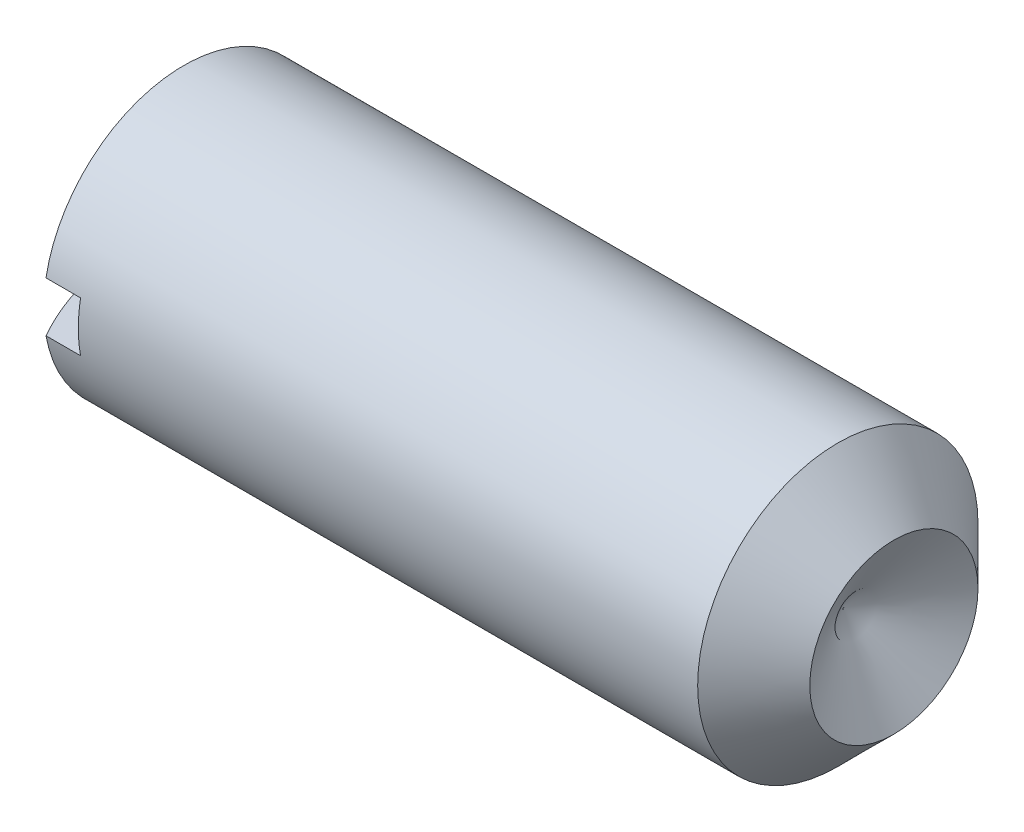
SolidWorks part; units mm, degrees
revolve "BaseBody" add sketch "BodySke" angle 360 about L5
sketch "BodySke" plane through (0, 0, 0) normal (0, 0, 1) x (1, 0, 0)
  line L0 (2.5522, -9.525) -> (47.1574, -9.525) construction
  line L1 (50.8, -5.715) -> (47.3661, 0) construction
  line L2 (2.5522, 9.525) -> (46.99, 9.525)
  line L3 (50.8, 5.715) -> (46.99, 9.525)
  line L4 (47.3661, 0) -> (0, 0)
  line L5 (-12.7, 0) -> (88.9, 0) construction
  line L6 (50.8, 5.715) -> (50.8, 19.05) construction
  line L7 (50.8, -5.715) -> (46.99, -9.525) construction
  line L8 (50.8, 5.715) -> (47.3661, 0)
  line L9 (2.0066, 12.7) -> (2.0066, -3.175) construction
  arc A1 (2.5522, 9.525) -> (0, 0) centre (19.05, 0) ccw
  dimension "Crown_radius" = 19.05
  dimension "Diameter" = 19.05
  dimension "Nose_ch_ang" = 45
  dimension "Length" = 50.8
  dimension "Cup_dia" = 11.43
  dimension "Cup_ang" = 118
  dimension "Advance" = 2.0066
cosmetic thread "ThreadCosmetic" [suppressed] parameters "Thread_minor"=16.0249
extrude "Slot" cut sketch "Sketch2" along normal blind 4.9022
sketch "Sketch2" plane through (0, 0, 0) normal (1, 0, 0) x (0, 0, -1)
  line L1 (9.525, -1.7018) -> (-9.525, -1.7018)
  line L2 (9.525, -1.7018) -> (9.525, 1.7018)
  line L3 (9.525, 1.7018) -> (-9.525, 1.7018)
  line L4 (-9.525, -1.7018) -> (-9.525, 1.7018)
  dimension "D1" = 19.05
  dimension "Slot_width" = 3.4036
  dimension "D3" = 9.525
  dimension "D2" = 1.7018
ref_plane "Plane1" through (0, 0, 0) normal (0, 0, 1) x (1, 0, 0)
ref_plane "Plane2" through (0, 0, 0) normal (0, 1, 0) x (1, 0, 0)
ref_plane "Plane3" through (0, 0, 0) normal (1, 0, 0) x (0, 0, -1)
sketch "ThdSchSke" plane through (0, 0, 0) normal (0, 0, 1) x (1, 0, 0)
  line L0 (2.5522, -8.0124) -> (1.4931, -9.525)
  line L1 (2.5522, -8.0124) -> (3.6113, -9.525)
  line L2 (3.6113, -9.525) -> (3.6113, -11.9063)
  line L3 (-3.175, 0) -> (5.1513, 0) construction
  line L4 (2.5522, -9.525) -> (2.5522, -1.7018) construction
  line L5 (3.6113, -11.9063) -> (1.4931, -11.9063)
  line L6 (1.4931, -11.9063) -> (1.4931, -9.525)
  dimension "Diameter" = 19.05
  dimension "Thread_minor" = 16.0249
revolve "ThreadSchematic" [suppressed] cut sketch "ThdSchSke" angle 360 about L3
pattern_linear "ThdSchPat" [suppressed]
equation "\"D1@Sketch2\" = \"Diameter@BodySke\""
equation "\"D3@Sketch2\" = \"D1@Sketch2\" / 2"
equation "\"D2@Sketch2\" = \"Slot_width@Sketch2\" / 2"
equation "\"Thread_minor@ThdSchSke\" = \"Thread_minor@ThreadCosmetic\""
equation "\"Diameter@ThdSchSke\" = \"Diameter@BodySke\""
equation "\"Overcut@ThdSchSke\" = \"Diameter@BodySke\" * 1.25"
equation "\"Num_threads@ThdSchPat\" = int ( ( \"Length@BodySke\" - ( \"Crown_radius@BodySke\" - sqr ( ( \"Crown_radius@BodySke\" * \"Crown_radius@BodySke\" ) - ( ( \"Diameter@BodySke\" * 0.5 ) * ( \"Diameter@BodySke\" * 0.5 ) ) ) ) - ( ( ( \"Diameter@BodySke\" - \"Cup_dia@BodySke\" ) * 0.5 ) * tan( \"Nose_ch_ang@BodySke\" * 0.017453292 ) ) ) / \"Advance@BodySke\" + 0.999 )  + 1"
equation "\"Advance@ThdSchPat\" = ( \"Length@BodySke\" - ( \"Crown_radius@BodySke\" - sqr ( ( \"Crown_radius@BodySke\" * \"Crown_radius@BodySke\" ) - ( ( \"Diameter@BodySke\" * 0.5 ) * ( \"Diameter@BodySke\" * 0.5 ) ) ) ) - ( ( ( \"Diameter@BodySke\" - \"Cup_dia@BodySke\" ) * 0.5 ) * tan( \"Nose_ch_ang@BodySke\" * 0.017453292 ) ) ) /  (\"Num_threads@ThdSchPat\" - 1) 'relax it"
equation "' \"Num_threads@ThdSchPat\" = \"Num_threads@ThdSchPat\" - sgn( \"Num_threads@ThdSchPat\" - 1) '---chamfered tips only---"
